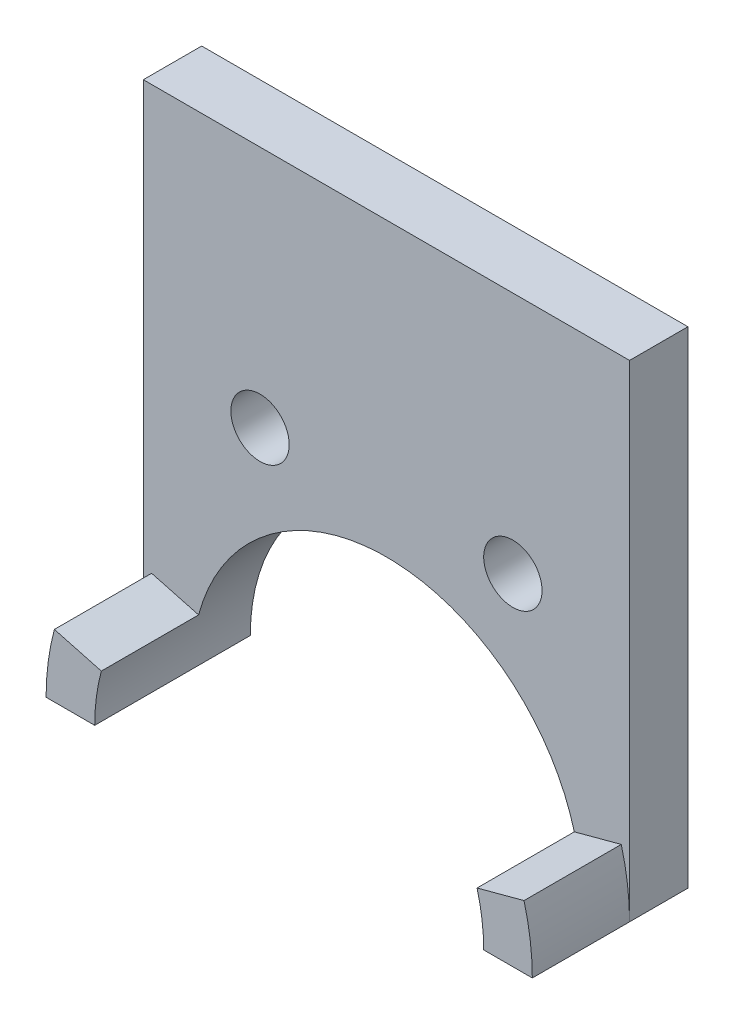
SolidWorks part; units mm, degrees
ref_plane "Płaszczyzna przednia" through (0, 0, 0) normal (0, 0, 1) x (1, 0, 0)
ref_plane "Płaszczyzna górna" through (0, 0, 0) normal (0, 1, 0) x (1, 0, 0)
ref_plane "Płaszczyzna prawa" through (0, 0, 0) normal (1, 0, 0) x (0, 0, -1)
sketch "Sketch1" plane through (0, 0, 0) normal (0, 0, 1) x (1, 0, 0)
  line L0 (25, 0) -> (-25, 0)
  circle A0 centre (0, 0) radius 20
  circle A1 centre (0, 0) radius 25
  dimension "D1" = 40
  dimension "D2" = 50
extrude "Boss-Extrude1" add sketch "Sketch1" along normal blind 6 contours L0 A1 A0
sketch "Sketch2" plane through (0, 0, 6) normal (0, 0, 1) x (1, 0, 0)
  line L0 (0, 0) -> (0, 9.8422) construction
  line L1 (0, 0) -> (-24.1481, 6.4705)
  line L2 (20, 0) -> (25, 0)
  line L3 (-25, 0) -> (-20, 0)
  line L4 (20, 0) -> (25, 0)
  line L5 (-25, 0) -> (-20, 0)
  line L6 (0, 0) -> (24.1481, 6.4705)
  arc A2 (25, 0) -> (-25, 0) centre (0, 0) ccw
  arc A3 (20, 0) -> (-20, 0) centre (0, 0) ccw
  arc A4 (25, 0) -> (-25, 0) centre (0, 0) ccw
  arc A5 (20, 0) -> (-20, 0) centre (0, 0) ccw
  line M7 (20, 0) -> (25, 0)
  arc M8 (25, 0) -> (-25, 0) centre (0, 0) ccw
  line M9 (-25, 0) -> (-20, 0)
  arc M10 (-20, 0) -> (20, 0) centre (0, 0) cw
  dimension "D2" = 15
  dimension "D1" = 0
extrude "Boss-Extrude2" add sketch "Sketch2" along normal blind 10 contours L1 M10 M8 M9 | L6 M10 M7 M8
sketch "Sketch3" plane through (0, 0, 0) normal (0, 0, -1) x (-1, 0, 0)
  line L0 (-25, 0) -> (-25, 50)
  line L1 (-25, 50) -> (25, 50)
  line L2 (25, 50) -> (25, 0)
  arc A0 (25, 0) -> (-25, 0) centre (0, 0) ccw construction
  arc A1 (25, 0) -> (-25, 0) centre (0, 0) ccw
  dimension "D1" = 50
extrude "Boss-Extrude3" add sketch "Sketch3" against normal up to surface (6 mm away) up to face at (0, 14.1617, 6)
sketch "Sketch4" plane through (0, 0, 6) normal (0, 0, 1) x (1, 0, 0)
  circle A0 centre (13, 25) radius 3 construction
  circle A1 centre (-13, 25) radius 3 construction
  circle A2 centre (13, 25) radius 3
  circle A3 centre (-13, 25) radius 3
extrude "Cut-Extrude1" cut sketch "Sketch4" against normal through all
